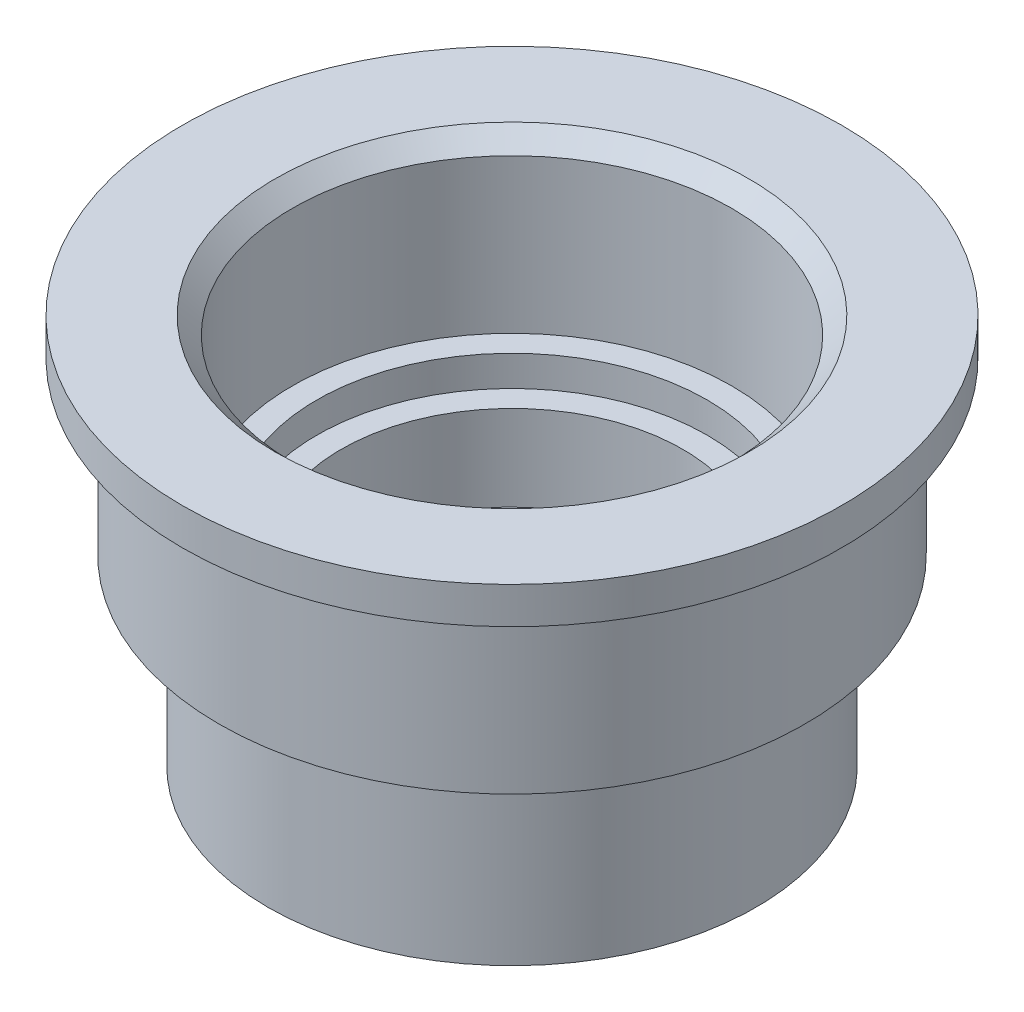
SolidWorks part; units mm, degrees
ref_plane "Plan de face" through (0, 0, 0) normal (0, 0, 1) x (1, 0, 0)
ref_plane "Plan de dessus" through (0, 0, 0) normal (0, 1, 0) x (1, 0, 0)
ref_plane "Plan de droite" through (0, 0, 0) normal (1, 0, 0) x (0, 0, -1)
sketch "Esquisse2" plane through (0, 0, 0) normal (0, 1, 0) x (1, 0, 0)
  circle A0 centre (0, 0) radius 10
  dimension "D1" = 20
extrude "Boss.-Extru.1" add sketch "Esquisse2" along normal blind 7.5 contours A0
sketch "Esquisse3" plane through (0, 7.5, 0) normal (0, 1, 0) x (1, 0, 0)
  circle A0 centre (0, 0) radius 12
  dimension "D1" = 24
extrude "Boss.-Extru.2" add sketch "Esquisse3" along normal blind 7 contours A0
sketch "Esquisse4" plane through (0, 14.5, 0) normal (0, 1, 0) x (1, 0, 0)
  circle A0 centre (0, 0) radius 13.5
  dimension "D1" = 27
extrude "Boss.-Extru.3" add sketch "Esquisse4" along normal blind 1.5 contours A0
sketch "Esquisse7" plane through (0, 0, 0) normal (0, -1, 0) x (1, 0, 0)
  circle A0 centre (0, 0) radius 5.5
  dimension "D1" = 11
extrude "Enlèv. mat.-Extru.1" cut sketch "Esquisse7" against normal blind 21.5
sketch "Esquisse8" plane through (0, 16, 0) normal (0, 1, 0) x (1, 0, 0)
  circle A0 centre (0, 0) radius 9
  dimension "D1" = 18
extrude "Enlèv. mat.-Extru.2" cut sketch "Esquisse8" against normal blind 7 contours A0
chamfer "Chanfrein1" distance 0.7 angle 45 1 edges at (0, 16, 9)
sketch "Esquisse9" plane through (0, 9, 0) normal (0, 1, 0) x (1, 0, 0)
  circle A0 centre (0, 0) radius 8
  dimension "D1" = 16
extrude "Enlèv. mat.-Extru.3" cut sketch "Esquisse9" against normal blind 1.25
sketch "Esquisse10" plane through (0, 7.75, 0) normal (0, 1, 0) x (1, 0, 0)
  circle A1 centre (0, 0) radius 7
  dimension "D1" = 14
extrude "Enlèv. mat.-Extru.4" cut sketch "Esquisse10" against normal blind 3.5
